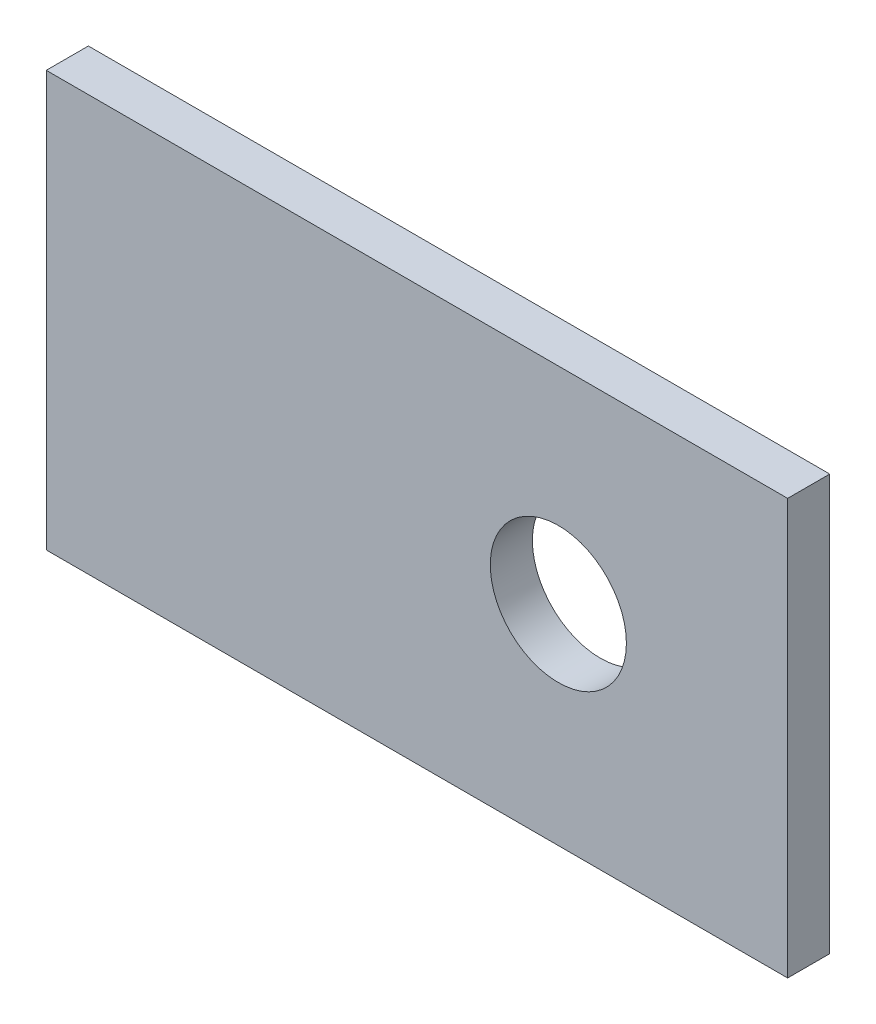
SolidWorks part; units mm, degrees
ref_plane "Front Plane" through (0, 0, 0) normal (0, 0, 1) x (1, 0, 0)
ref_plane "Top Plane" through (0, 0, 0) normal (0, 1, 0) x (1, 0, 0)
ref_plane "Right Plane" through (0, 0, 0) normal (1, 0, 0) x (0, 0, -1)
sketch "Sketch1" plane through (0, 0, 0) normal (0, 0, 1) x (1, 0, 0)
  line L1 (-26.415, -14.8) -> (26.415, -14.8)
  line L2 (-26.415, -14.8) -> (-26.415, 14.8)
  line L3 (-26.415, 14.8) -> (26.415, 14.8)
  line L4 (26.415, -14.8) -> (26.415, 14.8)
  line L5 (-26.415, -14.8) -> (26.415, 14.8) construction
  line L6 (-26.415, 14.8) -> (26.415, -14.8) construction
  point P0 (0, 0)
  dimension "D1" = 29.6
  dimension "D2" = 52.83
extrude "Boss-Extrude1" add sketch "Sketch1" along normal blind 3
sketch "Sketch2" plane through (0, 0, 3) normal (0, 0, 1) x (1, 0, 0)
  line L0 (-26.415, -14.8) -> (26.415, -14.8) construction
  line L1 (26.415, -14.8) -> (26.415, 14.8) construction
  circle A0 centre (10.075, 0.11) radius 4.85
  dimension "D1" = 9.7
  dimension "D2" = 14.91
  dimension "D3" = 16.34
extrude "Cut-Extrude1" cut sketch "Sketch2" against normal blind 10 contours A0
